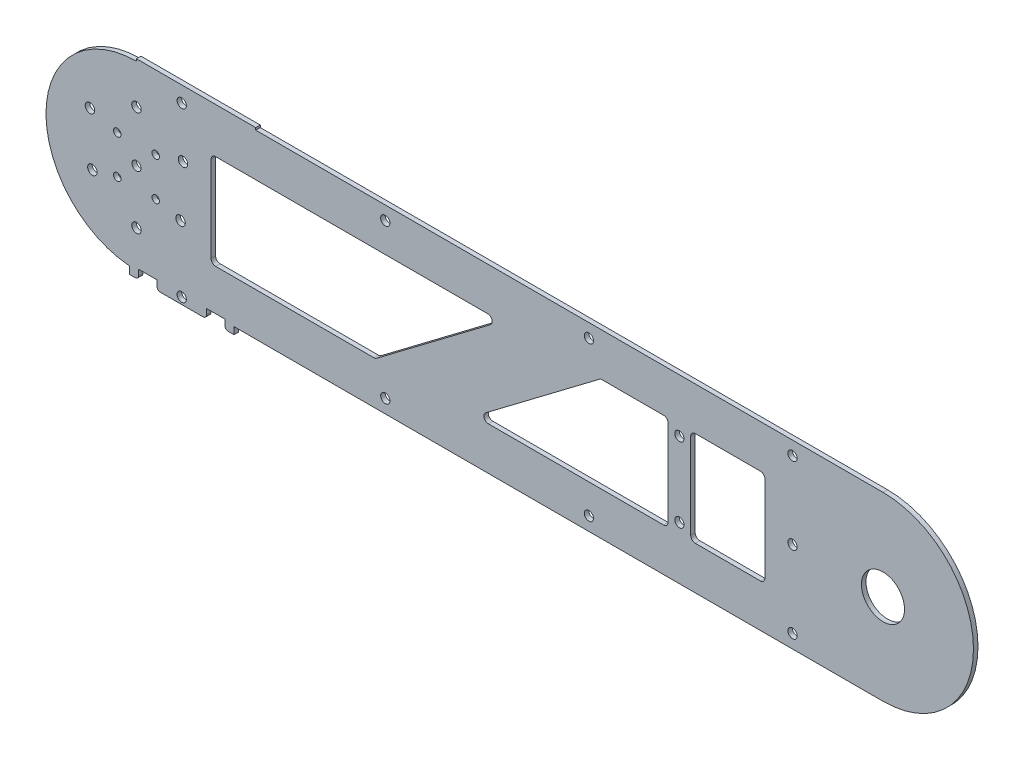
SolidWorks part; units mm, degrees
ref_plane "前视基准面" through (0, 0, 0) normal (0, 0, 1) x (1, 0, 0)
ref_plane "上视基准面" through (0, 0, 0) normal (0, 1, 0) x (1, 0, 0)
ref_plane "右视基准面" through (0, 0, 0) normal (1, 0, 0) x (0, 0, -1)
sketch "草图1" plane through (0, 0, 0) normal (0, 0, 1) x (1, 0, 0)
  line L0 (-1.4571, -0.1457) -> (37.8152, -22.8196) construction
  line L1 (-1.4571, -0.1457) -> (328.5429, -0.1457) construction
  line L3 (-1.4571, -40.1457) -> (328.5429, -40.1457)
  line L8 (-1.4571, 39.8543) -> (328.5429, 39.8543)
  line L9 (-1.4571, -0.1457) -> (-1.4571, -8.6457) construction
  line L10 (-1.4571, -8.6457) -> (7.0429, -8.6457) construction
  circle A0 centre (-1.4571, -0.1457) radius 23.75 construction
  circle A1 centre (-1.4571, -0.1457) radius 22.5 construction
  circle A2 centre (-1.4571, -23.8957) radius 2.1
  circle A3 centre (18.0284, -11.3957) radius 2.1
  circle A4 centre (-1.4571, -0.1457) radius 40 construction
  circle A6 centre (-1.4571, -0.1457) radius 2
  circle A12 centre (328.5429, -0.1457) radius 40 construction
  arc A16 (-1.4571, -40.1457) -> (-1.4571, 39.8543) centre (-1.4571, -0.1457) cw
  arc A21 (328.5429, -40.1457) -> (328.5429, 39.8543) centre (328.5429, -0.1457) ccw
  circle A22 centre (328.5429, -0.1457) radius 9.52
  circle A23 centre (288.5429, -0.1457) radius 2.05
  circle A24 centre (238.5429, 16.3543) radius 2.05
  circle A25 centre (238.5429, -16.6457) radius 2.05
  circle A26 centre (-20.9427, -11.3957) radius 2.1
  circle A27 centre (-22.0252, 11.7293) radius 2.1
  circle A28 centre (-1.4571, 22.3543) radius 2.1
  circle A29 centre (19.111, 11.7293) radius 2.1
  circle A37 centre (7.0429, -8.6457) radius 1.65
  circle A38 centre (-9.9571, -8.6457) radius 1.65
  circle A39 centre (-9.9571, 8.3543) radius 1.65
  circle A40 centre (7.0429, 8.3543) radius 1.65
  dimension "D1" = 45
  dimension "D2" = 3
  dimension "D3" = 4.2
  dimension "D4" = 19.04
  dimension "D5" = 80
  dimension "D6" = 80
  dimension "D7" = 4
  dimension "D11" = 4.1
  dimension "D12" = 47.5
  dimension "D13" = 4
  dimension "D8" = 330
  dimension "D9" = 50
  dimension "D10" = 16.5
extrude "凸台-拉伸1" add sketch "草图1" along normal blind 2 contours L3
sketch "草图3" plane through (0, 0, 2) normal (0, 0, 1) x (1, 0, 0)
  line L0 (-1.4571, 39.8543) -> (-1.4571, 40.8343)
  line L1 (41.6429, -39.4527) -> (-4.5571, -39.4527)
  line L2 (41.6429, -39.4527) -> (41.6429, -43.2699)
  line L3 (41.6429, -43.2699) -> (-4.5571, -43.2699)
  line L4 (-4.5571, -39.4527) -> (-4.5571, -43.2699)
  line L5 (-1.4571, 40.8343) -> (51.269, 40.8343)
  line L6 (51.269, 40.8343) -> (51.269, 39.8543)
  line L7 (-1.4571, -40.1457) -> (328.5429, -40.1457) construction
  line L8 (328.5429, 39.8543) -> (-1.4571, 39.8543) construction
  line L9 (51.269, 39.8543) -> (-1.4571, 39.8543)
  dimension "D1" = 3.1
  dimension "D2" = 46.2
  dimension "D3" = 3.1242
  dimension "D4" = 0.98
extrude "凸台-拉伸2" add sketch "草图3" against normal blind 2
sketch "草图2" plane through (0, 0, 2) normal (0, 0, 1) x (1, 0, 0)
  line L0 (18.5429, 33.8543) -> (198.5429, 33.8543) construction
  line L1 (108.5429, -34.1457) -> (198.5429, 33.8543) construction
  line L2 (18.5429, 33.8543) -> (18.5429, -34.1457) construction
  line L3 (18.5429, -34.1457) -> (108.5429, -34.1457) construction
  line L4 (31.5429, -21.1457) -> (104.1839, -21.1457)
  line L5 (104.1839, -21.1457) -> (159.7721, 20.8543)
  line L6 (31.5429, 20.8543) -> (159.7721, 20.8543)
  line L7 (31.5429, 20.8543) -> (31.5429, -21.1457)
  line L8 (108.5429, -34.1457) -> (288.5429, -34.1457) construction
  line L9 (288.5429, -34.1457) -> (288.5429, 33.8543) construction
  line L10 (288.5429, 33.8543) -> (198.5429, 33.8543) construction
  line L11 (276.3527, 20.8543) -> (203.7117, 20.8543) construction
  line L12 (148.1234, -21.1457) -> (203.7117, 20.8543)
  line L13 (148.1234, -21.1457) -> (276.3527, -21.1457) construction
  line L14 (276.3527, -21.1457) -> (276.3527, 20.8543)
  line L15 (233.5429, 20.8543) -> (233.5429, -21.1457)
  line L16 (243.5429, 20.8543) -> (243.5429, -21.1457)
  line L17 (238.5429, 16.3543) -> (238.5429, -16.6457) construction
  line L18 (233.5429, 20.8543) -> (203.7117, 20.8543)
  line L19 (243.5429, 20.8543) -> (276.3527, 20.8543)
  line L20 (243.5429, -21.1457) -> (276.3527, -21.1457)
  line L21 (233.5429, -21.1457) -> (148.1234, -21.1457)
  line L22 (41.6429, -40.1457) -> (328.5429, -40.1457) construction
  line L27 (18.5429, -34.1457) -> (18.5429, -40.1457) construction
  line L28 (41.6429, -40.1457) -> (328.5429, -40.1457) construction
  line L29 (29.4929, -39.2799) -> (37.5929, -39.2799)
  line L30 (29.4929, -39.2799) -> (29.4929, -41.3799)
  line L31 (29.4929, -41.3799) -> (37.5929, -41.3799) construction
  line L32 (37.5929, -39.2799) -> (37.5929, -41.3799)
  line L33 (29.4929, -39.2799) -> (37.5929, -41.3799) construction
  line L34 (29.4929, -41.3799) -> (37.5929, -39.2799) construction
  line L35 (-0.5071, -39.2799) -> (7.5929, -39.2799)
  line L36 (-0.5071, -39.2799) -> (-0.5071, -41.3799)
  line L37 (-0.5071, -41.3799) -> (7.5929, -41.3799) construction
  line L38 (7.5929, -39.2799) -> (7.5929, -41.3799)
  line L39 (-0.5071, -39.2799) -> (7.5929, -41.3799) construction
  line L40 (-0.5071, -41.3799) -> (7.5929, -39.2799) construction
  line L41 (-4.5571, -43.2699) -> (41.6429, -43.2699) construction
  line L42 (-0.5071, -41.3799) -> (-0.5071, -45.9593)
  line L43 (-0.5071, -45.9593) -> (7.5929, -45.9593)
  line L44 (7.5929, -45.9593) -> (7.5929, -41.3799)
  line L45 (29.4929, -41.3799) -> (29.4929, -45.9593)
  line L46 (29.4929, -45.9593) -> (37.5929, -45.9593)
  line L47 (37.5929, -45.9593) -> (37.5929, -41.3799)
  circle A0 centre (18.5429, 33.8543) radius 2.05
  circle A1 centre (108.5429, 33.8543) radius 2.05
  circle A2 centre (198.5429, 33.8543) radius 2.05
  circle A3 centre (288.5429, 33.8543) radius 2.05
  circle A4 centre (108.5429, -34.1457) radius 2.05
  circle A5 centre (198.5429, -34.1457) radius 2.05
  circle A6 centre (288.5429, -34.1457) radius 2.05
  arc A8 (-1.4571, 39.8543) -> (-4.5571, -40.0254) centre (-1.4571, -0.1457) ccw construction
  circle A9 centre (18.5429, -40.3299) radius 2.05
  point P2 (-1.4571, -0.1457)
  point P40 (33.5429, -40.3299)
  point P46 (3.5429, -40.3299)
  dimension "D1" = 4.1
  dimension "D6" = 15
  dimension "D12" = 4.1
  dimension "D14" = 68
  dimension "D2" = 34
  dimension "D3" = 20
  dimension "D4" = 10
  dimension "D5" = 20
  dimension "D7" = 8.1
  dimension "D8" = 2.1
  dimension "D9" = 15
  dimension "D10" = 8.1
  dimension "D11" = 2.1
  dimension "D13" = 6
  dimension "D15" = 2.94
extrude "切除-拉伸1" cut sketch "草图2" against normal blind 4
fillet "圆角1" radius 2 12 edges at (243.5429, -21.1457, 1) (243.5429, 20.8543, 1) (276.3527, -21.1457, 1) (276.3527, 20.8543, 1) (233.5429, -21.1457, 1) (233.5429, 20.8543, 1) (203.7117, 20.8543, 1) (148.1234, -21.1457, 1) (159.7721, 20.8543, 1) (104.1839, -21.1457, 1) (31.5429, -21.1457, 1) (31.5429, 20.8543, 1)
fillet "圆角2" radius 1.5 4 edges at (29.4929, -43.2699, 1) (37.5929, -43.2699, 1) (7.5929, -43.2699, 1) (-0.5071, -43.2699, 1)
